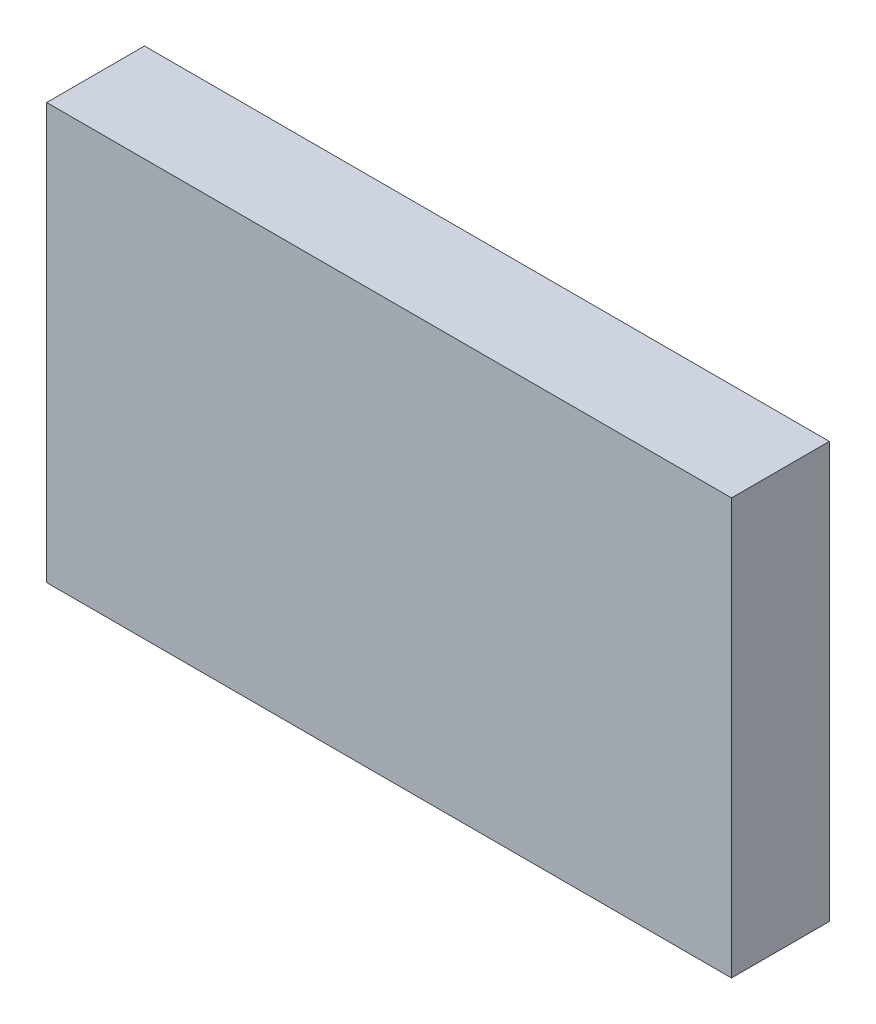
SolidWorks part; units mm, degrees
ref_plane "前视基准面" through (0, 0, 0) normal (0, 0, 1) x (1, 0, 0)
ref_plane "上视基准面" through (0, 0, 0) normal (0, 1, 0) x (1, 0, 0)
ref_plane "右视基准面" through (0, 0, 0) normal (1, 0, 0) x (0, 0, -1)
sketch "草图1" plane through (0, 0, 0) normal (0, 0, 1) x (1, 0, 0)
  line L1 (0, 0) -> (140, 0)
  line L2 (0, 0) -> (0, -85)
  line L3 (0, -85) -> (140, -85)
  line L4 (140, 0) -> (140, -85)
  dimension "D1" = 140
  dimension "D2" = 85
extrude "凸台-拉伸1" add sketch "草图1" along normal blind 20
